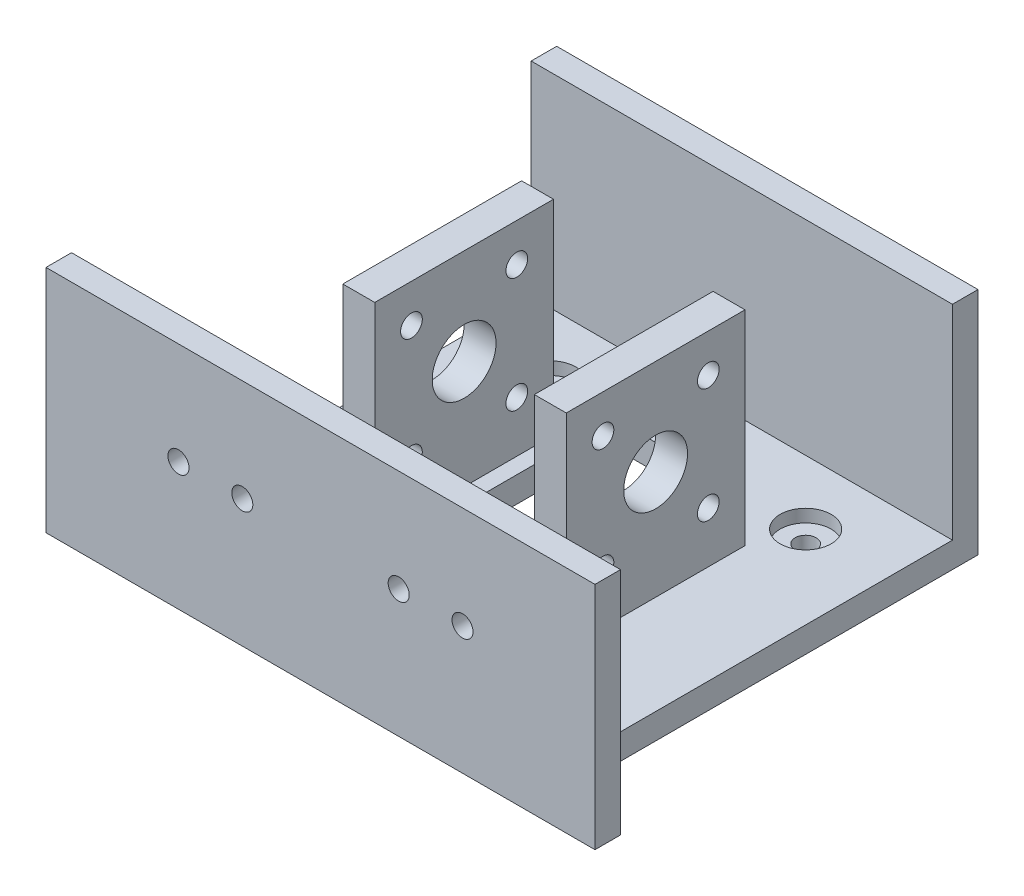
SolidWorks part; units mm, degrees
ref_plane "Front Plane" through (0, 0, 0) normal (0, 0, 1) x (1, 0, 0)
ref_plane "Top Plane" through (0, 0, 0) normal (0, 1, 0) x (1, 0, 0)
ref_plane "Right Plane" through (0, 0, 0) normal (1, 0, 0) x (0, 0, -1)
sketch "Sketch1" plane through (0, 0, 0) normal (0, 1, 0) x (1, 0, 0)
  line L0 (0, 0) -> (0, -14.43) construction
  line L1 (-37.5, 20) -> (37.5, 20)
  line L2 (-37.5, 20) -> (-37.5, -20)
  line L3 (-37.5, -20) -> (37.5, -20)
  line L4 (37.5, 20) -> (37.5, -20)
  line L5 (-37.5, 20) -> (37.5, -20) construction
  line L6 (-37.5, -20) -> (37.5, 20) construction
  line L7 (0, 0) -> (6.508, 0) construction
  line L8 (-5, 10) -> (5, 10)
  line L9 (-5, 10) -> (-5, -10)
  line L10 (-5, -10) -> (5, -10)
  line L11 (5, 10) -> (5, -10)
  line L12 (-5, 10) -> (5, -10) construction
  line L13 (-5, -10) -> (5, 10) construction
  circle A0 centre (-21, 0) radius 5
  circle A1 centre (-30, 8.25) radius 1.7
  circle A2 centre (-12, 8.25) radius 1.7
  circle A3 centre (-12, -8.25) radius 1.7
  circle A4 centre (-30, -8.25) radius 1.7
  circle A5 centre (12, 8.25) radius 1.7
  circle A6 centre (12, -8.25) radius 1.7
  circle A7 centre (21, 0) radius 5
  circle A8 centre (30, -8.25) radius 1.7
  circle A9 centre (30, 8.25) radius 1.7
  point P0 (0, 0)
  dimension "D3" = 10
  dimension "D4" = 16.5
  dimension "D5" = 16.5
  dimension "D6" = 18
  dimension "D9" = 10
  dimension "D11" = 20
  dimension "D13" = 7.5
  dimension "D17" = 3.4
  dimension "D19" = 11.75
  dimension "D20" = 11.75
  dimension "D1" = 75
  dimension "D2" = 40
  dimension "D10" = 10
  dimension "D7" = 2
  dimension "D8" = 2
extrude "Boss-Extrude1" add sketch "Sketch1" along normal blind 3
sketch "Sketch2" plane through (0, 3, 0) normal (0, 1, 0) x (1, 0, 0)
  line L0 (-37.5, 20) -> (-37.5, -20) construction
  line L1 (-33.5, 14) -> (33.5, 14)
  line L2 (-33.5, 14) -> (-33.5, -14)
  line L3 (-33.5, -14) -> (33.5, -14)
  line L4 (33.5, 14) -> (33.5, -14)
  line L5 (37.5, -20) -> (37.5, 20) construction
  line L6 (37.5, 20) -> (-37.5, 20) construction
  line L7 (-37.5, -20) -> (37.5, -20) construction
  dimension "D1" = 4
  dimension "D2" = 4
  dimension "D3" = 6
  dimension "D4" = 6
extrude "Cut-Extrude1" cut sketch "Sketch2" against normal through all both and the other way through all
sketch "Sketch3" plane through (0, 3, 0) normal (0, 1, 0) x (1, 0, 0)
  line L1 (37.5, 20) -> (-37.5, 20)
  line L2 (37.5, 20) -> (37.5, 35)
  line L3 (37.5, 35) -> (-37.5, 35)
  line L4 (-37.5, 20) -> (-37.5, 35)
  line L5 (-37.5, -20) -> (37.5, -20)
  line L6 (-37.5, -20) -> (-37.5, -35)
  line L7 (-37.5, -35) -> (37.5, -35)
  line L8 (37.5, -20) -> (37.5, -35)
  line L10 (-37.5, 20) -> (-33.5, 20)
  line L11 (-37.5, 20) -> (-37.5, -20)
  line L12 (-37.5, -20) -> (-33.5, -20)
  line L13 (-33.5, 20) -> (-33.5, -20)
  line L14 (37.5, 20) -> (33.5, 20)
  line L15 (37.5, 20) -> (37.5, -20)
  line L16 (37.5, -20) -> (33.5, -20)
  line L17 (33.5, 20) -> (33.5, -20)
  line M3 (-33.5, -14) -> (-33.5, 14)
  line M5 (33.5, 14) -> (33.5, -14)
  line M11 (37.5, -20) -> (37.5, 20)
  line M12 (37.5, 20) -> (-37.5, 20)
  line M13 (-37.5, 20) -> (-37.5, -20)
  line M14 (-37.5, -20) -> (37.5, -20)
  dimension "D1" = 15
  dimension "D2" = 15
extrude "Boss-Extrude3" add sketch "Sketch3" along normal blind 110 and the other way blind 3 contours L8 L5 L6 L7 M14 | L4 L1 L2 L3 M12 | L17 M12 M5 M14 M11 | L13 L1 M13 M14 M3
sketch "Sketch6" plane through (0, 3, 0) normal (0, 1, 0) x (1, 0, 0)
  line L0 (-37.5, -35) -> (37.5, -35) construction
  line L1 (-33.5, -20) -> (33.5, -20)
  line L2 (-33.5, -20) -> (-33.5, -31)
  line L3 (-33.5, -31) -> (33.5, -31)
  line L4 (33.5, -20) -> (33.5, -31)
  line L5 (33.5, 20) -> (-33.5, 20)
  line L6 (33.5, 20) -> (33.5, 31)
  line L7 (33.5, 31) -> (-33.5, 31)
  line L8 (-33.5, 20) -> (-33.5, 31)
  line L9 (37.5, 35) -> (-37.5, 35) construction
  dimension "D1" = 4
  dimension "D2" = 4
extrude "Cut-Extrude4" cut sketch "Sketch6" along normal through all
sketch "Sketch7" plane through (-37.5, 0, 0) normal (-1, 0, 0) x (0, 0, 1)
  line L0 (35, 0) -> (35, 113) construction
  line L1 (-35, 113) -> (35, 113)
  line L2 (-35, 113) -> (-35, 76)
  line L3 (-35, 76) -> (35, 76)
  line L4 (35, 113) -> (35, 76)
  dimension "D1" = 37
extrude "Boss-Extrude4" add sketch "Sketch7" along normal blind 45
ref_plane "Plane1" through (0, 0, 0) normal (1, 0, 0) x (0, 0, -1)
mirror "Mirror2" about plane through (0, 0, 0) normal (1, 0, 0) of "Boss-Extrude4"
sketch "Sketch8" plane through (0, 113, 0) normal (0, 1, 0) x (1, 0, 0)
  line L0 (-82.5, -35) -> (-82.5, 35) construction
  line L1 (-33.5, 31) -> (-78.5, 31)
  line L2 (-33.5, 31) -> (-33.5, -31)
  line L3 (-33.5, -31) -> (-78.5, -31)
  line L4 (-78.5, 31) -> (-78.5, -31)
  line L5 (33.5, -31) -> (78.5, -31)
  line L6 (33.5, -31) -> (33.5, 31)
  line L7 (33.5, 31) -> (78.5, 31)
  line L8 (78.5, -31) -> (78.5, 31)
  line L9 (82.5, -35) -> (82.5, 35) construction
  dimension "D1" = 4
  dimension "D2" = 4
extrude "Cut-Extrude6" cut sketch "Sketch8" against normal blind 29
sketch "Sketch9" plane through (-82.5, 0, 0) normal (-1, 0, 0) x (0, 0, 1)
  line L18 (-31, 84) -> (31, 84) construction
  line L19 (-19, 84) -> (19, 84)
  line L20 (-19, 84) -> (-19, 112.5)
  line L21 (-19, 112.5) -> (19, 112.5)
  line L22 (19, 84) -> (19, 112.5)
  line L25 (-31, 84) -> (-31, 113) construction
  dimension "D1" = 38
  dimension "D2" = 12
  dimension "D3" = 28.5
sketch "Sketch11" plane through (0, 0, 35) normal (0, 0, 1) x (1, 0, 0)
  line L0 (82.5, 76) -> (82.5, 113) construction
  line L1 (-82.5, 76) -> (-37.5, 76)
  line L2 (-82.5, 76) -> (-82.5, 80)
  line L3 (-82.5, 80) -> (-37.5, 80)
  line L4 (-37.5, 76) -> (-37.5, 80)
  line L5 (37.5, 76) -> (82.5, 76)
  line L6 (37.5, 76) -> (37.5, 80)
  line L7 (37.5, 80) -> (82.5, 80)
  line L8 (82.5, 76) -> (82.5, 80)
  line L11 (-78.5, 84) -> (-33.5, 84) construction
  line L12 (33.5, 84) -> (78.5, 84) construction
  dimension "D1" = 4
  dimension "D2" = 4
extrude "Cut-Extrude9" cut sketch "Sketch11" against normal through all
extrude "Cut-Extrude10" cut sketch "Sketch9" against normal through all
sketch "Sketch13" plane through (0, 84, 0) normal (0, 1, 0) x (1, 0, 0)
  line L0 (-78.5, 31) -> (-78.5, -31) construction
  line L1 (-41.5, 19) -> (-36.5, 19)
  line L2 (-41.5, 19) -> (-41.5, -19)
  line L3 (-41.5, -19) -> (-36.5, -19)
  line L4 (-36.5, 19) -> (-36.5, -19)
  line L7 (78.5, 31) -> (-78.5, 31) construction
  line L13 (-41.5, -19) -> (-41.5, 19)
  line L17 (-82.5, -19) -> (-107.5, -19)
  line L18 (-82.5, -19) -> (-82.5, 19)
  line L19 (-82.5, 19) -> (-107.5, 19)
  line L20 (-107.5, -19) -> (-107.5, 19)
  line L21 (-107.5, 19) -> (-61, 19)
  line L22 (-107.5, 19) -> (-107.5, -19)
  line L23 (-107.5, -19) -> (-61, -19)
  line L24 (-61, 19) -> (-61, -19)
  dimension "D1" = 37
  dimension "D2" = 5
  dimension "D3" = 38
  dimension "D4" = 12
  dimension "D5" = 25
  dimension "D6" = 46.5
extrude "Boss-Extrude5" add sketch "Sketch13" along normal blind 32 contours L4 L1 L2 L3
sketch "Sketch14" plane through (-41.5, 0, 0) normal (-1, 0, 0) x (0, 0, 1)
  line L0 (-19, 116) -> (-19, 84) construction
  line L4 (19, 112.5) -> (-19, 112.5) construction
  circle A0 centre (0, 101) radius 5
  circle A1 centre (-8.25, 110) radius 1.7
  circle A2 centre (8.25, 110) radius 1.7
  circle A3 centre (8.25, 92) radius 1.7
  circle A4 centre (-8.25, 92) radius 1.7
  dimension "D1" = 19
  dimension "D2" = 8.25
  dimension "D3" = 10
  dimension "D6" = 3.4
  dimension "D7" = 11.5
  dimension "D8" = 18
  dimension "D9" = 16.5
  dimension "D10" = 9
  dimension "D11" = 8.25
  dimension "D4" = 2
  dimension "D5" = 2
extrude "Cut-Extrude11" cut sketch "Sketch14" against normal blind 32
mirror "Mirror4" about plane through (0, 0, 0) normal (1, 0, 0) of "Boss-Extrude5", "Cut-Extrude11"
sketch "Sketch15" plane through (0, 113, 0) normal (0, 1, 0) x (1, 0, 0)
  line L1 (-82.5, 35) -> (82.5, 35)
  line L2 (-82.5, 35) -> (-82.5, -35)
  line L3 (-82.5, -35) -> (82.5, -35)
  line L4 (82.5, 35) -> (82.5, -35)
  line L5 (-78.5, 31) -> (78.5, 31)
  line L6 (-78.5, 31) -> (-78.5, -31)
  line L7 (-78.5, -31) -> (78.5, -31)
  line L8 (78.5, 31) -> (78.5, -31)
extrude "Boss-Extrude6" add sketch "Sketch15" along normal blind 3
sketch "Sketch16" plane through (0, 0, 35) normal (0, 0, 1) x (1, 0, 0)
  line L1 (-10, 14.0464) -> (10, 14.0464)
  line L2 (-10, 14.0464) -> (-10, 9.2258)
  line L3 (-10, 9.2258) -> (10, 9.2258)
  line L4 (10, 14.0464) -> (10, 9.2258)
  line L5 (-37.5, 0) -> (-37.5, 80) construction
  dimension "D1" = 20
  dimension "D2" = 27.5
extrude "Cut-Extrude12" cut sketch "Sketch16" against normal through all
sketch "Sketch18" plane through (0, 0, 35) normal (0, 0, 1) x (1, 0, 0)
  line L0 (41.5, 116) -> (41.5, 84) construction
  line L2 (33.5, 84) -> (78.5, 84) construction
  circle A0 centre (52.25, 100) radius 1.65
  dimension "D1" = 10.75
  dimension "D2" = 16
  dimension "D3" = 3.3
extrude "Cut-Extrude14" cut sketch "Sketch18" against normal through all
mirror "Mirror5" about plane through (0, 0, 0) normal (1, 0, 0) of "Cut-Extrude14"
mirror "Mirror6" about plane through (0, 116, 0) normal (0, 1, 0) of "Mirror4", "Boss-Extrude5", "Cut-Extrude11"
sketch "Sketch19" plane through (82.5, 0, 0) normal (1, 0, 0) x (0, 0, -1)
  line L0 (19, 148) -> (19, 84) construction
  line L1 (-19, 112.5) -> (19, 112.5)
  line L2 (-19, 112.5) -> (-19, 116)
  line L3 (-19, 116) -> (19, 116)
  line L4 (19, 112.5) -> (19, 116)
extrude "Cut-Extrude15" cut sketch "Sketch19" against normal blind 10
mirror "Mirror7" about plane through (0, 0, 0) normal (1, 0, 0) of "Cut-Extrude15"
sketch "Sketch20" plane through (0, 3, 0) normal (0, 1, 0) x (1, 0, 0)
  line L0 (33.5, 31) -> (-33.5, 31) construction
  line L1 (-5, -10) -> (5, -10)
  line L2 (-5, -10) -> (-5, 10)
  line L3 (-5, 10) -> (5, 10)
  line L4 (5, -10) -> (5, 10)
  line L5 (-5, -10) -> (5, 10) construction
  line L6 (-5, 10) -> (5, -10) construction
  line L7 (0, 0) -> (0, 17.5) construction
  line L8 (-37.5, 20) -> (37.5, 20)
  line L9 (-37.5, 20) -> (-37.5, -20)
  line L10 (-37.5, -20) -> (37.5, -20)
  line L11 (37.5, 20) -> (37.5, -20)
  line L12 (-37.5, 20) -> (37.5, -20) construction
  line L13 (-37.5, -20) -> (37.5, 20) construction
  line L14 (0, -34.1) -> (0, 34.1) construction
  circle A1 centre (-12, 17.5) radius 1.2
  circle A2 centre (-12, -17.5) radius 1.2
  circle A3 centre (-24, -17.5) radius 1.2
  circle A4 centre (-24, 17.5) radius 1.2
  circle A5 centre (12, -17.5) radius 1.2
  circle A6 centre (24, -17.5) radius 1.2
  circle A7 centre (12, 17.5) radius 1.2
  circle A8 centre (24, 17.5) radius 1.2
  point P2 (0, 0)
  point P10 (0, 0)
  dimension "D1" = 7
  dimension "D2" = 10
  dimension "D4" = 2.5
  dimension "D7" = 35
  dimension "D8" = 7
  dimension "D9" = 2.4
  dimension "D11" = 12
  dimension "D3" = 21
  dimension "D5" = 75
  dimension "D6" = 40
  dimension "D10" = 2
extrude "Cut-Extrude16" cut sketch "Sketch20" against normal blind 10 contours A4 | A1 | A7 | A3 | A2 | A8 | A5 | A6
sketch "Sketch21" plane through (0, 0, 35) normal (0, 0, 1) x (1, 0, 0)
  line L0 (0, -34.1) -> (0, 34.1) construction
  line L1 (37.5, 0) -> (27.5, 0)
  line L2 (37.5, 0) -> (37.5, 80)
  line L3 (37.5, 80) -> (27.5, 80)
  line L4 (27.5, 0) -> (27.5, 80)
  line L5 (-27.5, 0) -> (-27.5, 80)
  line L6 (-37.5, 80) -> (-27.5, 80)
  line L7 (-37.5, 0) -> (-37.5, 80)
  line L8 (-37.5, 0) -> (-27.5, 0)
  dimension "D1" = 10
  dimension "D2" = 80
extrude "Cut-Extrude17" cut sketch "Sketch21" against normal through all
sketch "Sketch22" plane through (0, 0, 35) normal (0, 0, 1) x (1, 0, 0)
  line L1 (-27.5, 0) -> (27.5, 0)
  line L2 (-27.5, 0) -> (-27.5, 80)
  line L3 (-27.5, 80) -> (27.5, 80)
  line L4 (27.5, 0) -> (27.5, 80)
extrude "Cut-Extrude18" cut sketch "Sketch22" against normal through all
sketch "Sketch23" plane through (0, 80, 0) normal (0, -1, 0) x (1, 0, 0)
  line L1 (-33.5, 31) -> (33.5, 31)
  line L2 (-33.5, 31) -> (-33.5, -31)
  line L3 (-33.5, -31) -> (33.5, -31)
  line L4 (33.5, 31) -> (33.5, -31)
extrude "Boss-Extrude7" add sketch "Sketch23" against normal blind 4
sketch "Sketch24" plane through (0, 84, 0) normal (0, 1, 0) x (1, 0, 0)
  line L10 (0, 0) -> (0, 16.8876) construction
  line L11 (0, -34.1) -> (0, 34.1) construction
  circle A0 centre (0, 0) radius 10
  circle A1 centre (-20, 21) radius 1.65
  circle A2 centre (-20, -21) radius 1.65
  circle A3 centre (20, -21) radius 1.65
  circle A4 centre (20, 21) radius 1.65
  dimension "D1" = 20
  dimension "D2" = 21
  dimension "D3" = 20
  dimension "D4" = 21
  dimension "D5" = 3.3
  dimension "D6" = 3.3
extrude "Cut-Extrude19" cut sketch "Sketch24" against normal through all
sketch "Sketch25" plane through (0, 0, -35) normal (0, 0, -1) x (-1, 0, 0)
  line L0 (33.5, 84) -> (33.5, 80)
  line L5 (-82.5, 80) -> (82.5, 80) construction
  line L7 (33.5, 80) -> (82.5, 80)
  line L8 (33.5, 80) -> (33.5, 116)
  line L9 (33.5, 116) -> (82.5, 116)
  line L10 (82.5, 80) -> (82.5, 116)
  line M2 (-82.5, 80) -> (82.5, 80)
  line M3 (82.5, 80) -> (82.5, 116)
  line M4 (82.5, 116) -> (-82.5, 116)
  circle M5 centre (52.25, 100) radius 1.65
extrude "Cut-Extrude21" cut sketch "Sketch25" against normal blind 16 contours L8 L0 M2 M3 M4 M5
mirror "Mirror8" about plane through (0, 0, 0) normal (1, 0, 0) of "Cut-Extrude21"
sketch "Sketch26" plane through (0, 0, -19) normal (0, 0, -1) x (-1, 0, 0)
  line L0 (78.5, 116) -> (-78.5, 116) construction
  line L1 (82.5, 80) -> (68, 80)
  line L2 (82.5, 80) -> (82.5, 116)
  line L3 (82.5, 116) -> (68, 116)
  line L4 (68, 80) -> (68, 116)
  dimension "D1" = 14.5
extrude "Cut-Extrude22" cut sketch "Sketch26" against normal through all
mirror "Mirror9" about plane through (0, 0, 0) normal (1, 0, 0) of "Cut-Extrude22"
sketch "Sketch27" plane through (0, 0, -19) normal (0, 0, -1) x (-1, 0, 0)
  line L1 (-41.5, 148) -> (-36.5, 148)
  line L2 (-41.5, 148) -> (-41.5, 84)
  line L3 (-41.5, 84) -> (-36.5, 84)
  line L4 (-36.5, 148) -> (-36.5, 84)
extrude "Cut-Extrude23" cut sketch "Sketch27" against normal blind 43
sketch "Sketch28" plane through (0, 84, 0) normal (0, 1, 0) x (1, 0, 0)
  line L5 (-68, -31) -> (68, -31) construction
  line L6 (68, 19) -> (33.5, 19)
  line L7 (68, 19) -> (68, -31)
  line L8 (68, -31) -> (33, -31)
  line L9 (33, 19) -> (33, -31)
  line L11 (33.5, 35) -> (33, 35)
  line L12 (33.5, 35) -> (33.5, 19)
  line L14 (33, 35) -> (33, 19)
  dimension "D1" = 0
  dimension "D2" = 35
extrude "Cut-Extrude24" cut sketch "Sketch28" against normal through all both and the other way through all
sketch "Sketch29" plane through (0, 84, 0) normal (0, 1, 0) x (1, 0, 0)
  line L0 (0, -34.1) -> (0, 34.1) construction
  line L2 (0, 0) -> (13.2142, 0)
  circle A0 centre (-20, 21) radius 4
  circle A1 centre (20, 21) radius 4
  circle A2 centre (20, -21) radius 4
  circle A3 centre (-20, -21) radius 4
  circle M12 centre (20, 21) radius 1.65
  circle M13 centre (20, -21) radius 1.65
  circle M14 centre (-20, 21) radius 1.65
  circle M15 centre (-20, -21) radius 1.65
extrude "Cut-Extrude25" cut sketch "Sketch29" against normal blind 2 contours A1 M12 | A0 M14 | A3 M15 | A2 M13
sketch "Sketch30" plane through (0, 84, 0) normal (0, 1, 0) x (1, 0, 0)
  line L1 (0, -34.1) -> (0, 34.1) construction
  line L3 (12.5, -14) -> (17.5, -14)
  line L4 (12.5, -14) -> (12.5, 14)
  line L5 (12.5, 14) -> (17.5, 14)
  line L6 (17.5, -14) -> (17.5, 14)
  line L8 (-68, -31) -> (68, -31) construction
  line L9 (33, 31) -> (-33.5, 31) construction
  point P6 (0, 0)
  dimension "D1" = 12.5
  dimension "D2" = 5
  dimension "D3" = 17
  dimension "D4" = 17
extrude "Boss-Extrude8" add sketch "Sketch30" along normal blind 32
sketch "Sketch32" plane through (17.5, 0, 0) normal (1, 0, 0) x (0, 0, -1)
  circle A0 centre (0, 101) radius 5
  circle A1 centre (8.25, 110) radius 1.7
  circle A2 centre (-8.25, 110) radius 1.7
  circle A3 centre (-8.25, 92) radius 1.7
  circle A4 centre (8.25, 92) radius 1.7
  dimension "D1" = 2
  dimension "D2" = 2
extrude "Cut-Extrude26" cut sketch "Sketch32" against normal blind 32
mirror "Mirror11" about plane through (0, 0, 0) normal (1, 0, 0) of "Cut-Extrude24"
mirror "Mirror16" about plane through (0, 0, 0) normal (1, 0, 0) of "Boss-Extrude8"
mirror "Mirror18" about plane through (0, 0, 0) normal (1, 0, 0) of "Cut-Extrude26"
sketch "Sketch34" plane through (0, 84, 0) normal (0, 1, 0) x (1, 0, 0)
  line L1 (-10, 0) -> (10, 0)
  line L2 (-10, 0) -> (-10, 21)
  line L3 (-10, 21) -> (10, 21)
  line L4 (10, 0) -> (10, 21)
  line L5 (-10, 0) -> (10, 0)
  line L6 (-10, 0) -> (-10, -21)
  line L7 (-10, -21) -> (10, -21)
  line L8 (10, 0) -> (10, -21)
  circle A0 centre (0, 0) radius 10 construction
  circle M13 centre (0, 0) radius 10
  dimension "D1" = 21
  dimension "D2" = 21
extrude "Cut-Extrude27" cut sketch "Sketch34" against normal blind 32 contours L4 L3 L2 M13 | L8 L6 L7 M13
sketch "Sketch36" plane through (0, 0, 35) normal (0, 0, 1) x (1, 0, 0)
  line L0 (0, -34.1) -> (0, 34.1) construction
  line L1 (68, 80) -> (-68, 80) construction
  line L2 (68, 116) -> (68, 80) construction
  circle A3 centre (22.25, 100) radius 1.65
  circle A4 centre (12.25, 100) radius 1.65
  circle A5 centre (-12.25, 100) radius 1.65
  circle A6 centre (-22.25, 100) radius 1.65
  dimension "D2" = 20
  dimension "D3" = 10
  dimension "D4" = 55.75
  dimension "D1" = 3.3
extrude "Cut-Extrude28" cut sketch "Sketch36" against normal blind 10
sketch "Sketch37" plane through (0, 0, 35) normal (0, 0, 1) x (1, 0, 0)
  line L0 (0, -34.1) -> (0, 34.1) construction
  line L1 (48.9566, 103.0877) -> (55.5434, 103.0877)
  line L2 (48.9566, 103.0877) -> (48.9566, 96.9123)
  line L3 (48.9566, 96.9123) -> (55.5434, 96.9123)
  line L4 (55.5434, 103.0877) -> (55.5434, 96.9123)
  line L5 (48.9566, 103.0877) -> (55.5434, 96.9123) construction
  line L6 (48.9566, 96.9123) -> (55.5434, 103.0877) construction
  line L7 (-48.9566, 96.9123) -> (-55.5434, 96.9123)
  line L8 (-55.5434, 103.0877) -> (-55.5434, 96.9123)
  line L9 (-48.9566, 103.0877) -> (-55.5434, 103.0877)
  line L10 (-48.9566, 103.0877) -> (-48.9566, 96.9123)
  line L11 (-48.9566, 96.9123) -> (-55.5434, 103.0877) construction
  line L12 (-48.9566, 103.0877) -> (-55.5434, 96.9123) construction
  point P0 (52.25, 100)
  point P12 (-52.25, 100)
extrude "Boss-Extrude9" add sketch "Sketch37" against normal blind 4
sketch "Sketch38" plane through (0, 0, 35) normal (0, 0, 1) x (1, 0, 0)
  line L0 (68, 80) -> (-68, 80) construction
  line L1 (-68, 116) -> (-43, 116)
  line L2 (-68, 116) -> (-68, 80)
  line L3 (-68, 80) -> (-43, 80)
  line L4 (-43, 116) -> (-43, 80)
  line L6 (68, 116) -> (43, 116)
  line L7 (68, 116) -> (68, 80)
  line L8 (68, 80) -> (43, 80)
  line L9 (43, 116) -> (43, 80)
  dimension "D1" = 25
  dimension "D2" = 25
extrude "Cut-Extrude29" cut sketch "Sketch38" against normal blind 10
